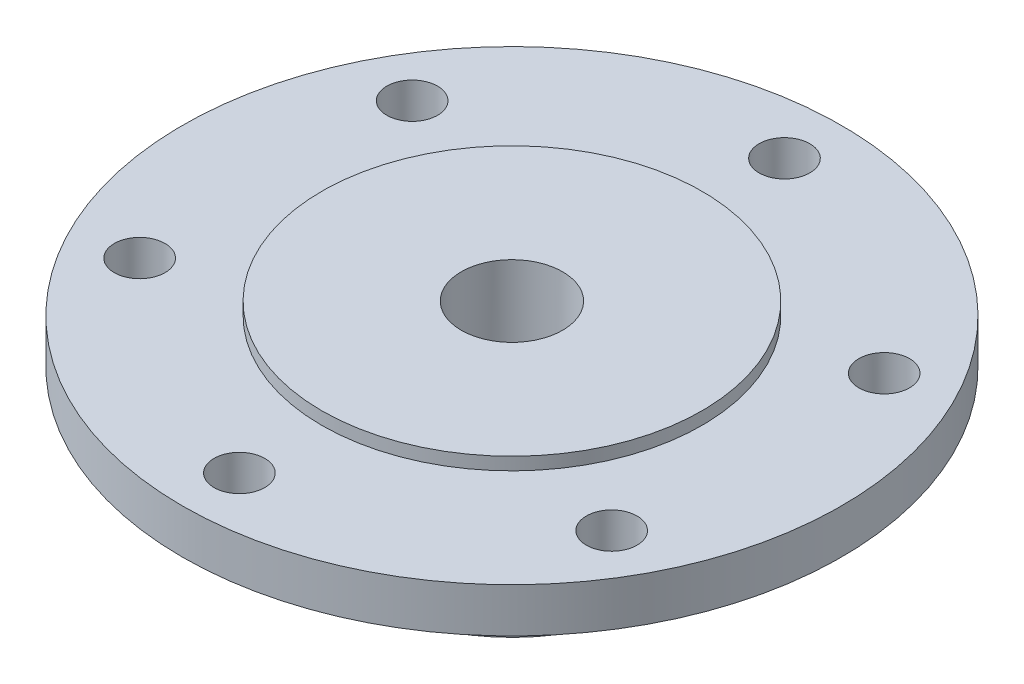
SolidWorks part; units mm, degrees
ref_plane "Front Plane" through (0, 0, 0) normal (0, 0, 1) x (1, 0, 0)
ref_plane "Top Plane" through (0, 0, 0) normal (0, 1, 0) x (1, 0, 0)
ref_plane "Right Plane" through (0, 0, 0) normal (1, 0, 0) x (0, 0, -1)
sketch "Sketch1" plane through (0, 0, 0) normal (0, 0, 1) x (1, 0, 0)
  line L0 (0, 11.2335) -> (0, -11.2335) construction
  line L1 (0, 7.25) -> (0, -7.25)
  line L2 (0, 7.25) -> (15, 7.25)
  line L3 (15, 7.25) -> (15, 6.25)
  line L4 (15, 6.25) -> (26, 6.25)
  line L5 (26, 6.25) -> (26, 2.75)
  line L6 (26, 2.75) -> (12, 2.75)
  line L7 (0, -7.25) -> (12, -7.25)
  line L8 (12, -7.25) -> (12, 2.75)
  point P4 (0, 0)
  point P8 (0, 0)
  dimension "D1" = 12
  dimension "D2" = 15
  dimension "D3" = 26
  dimension "D4" = 2.75
  dimension "D5" = 6.25
  dimension "D6" = 7.25
revolve "Revolve1" add sketch "Sketch1" angle 360 about L0
hole_wizard "Tap Drill for M12x1.25 Tap1" positions "Sketch3" profile "Sketch4" hole size "M12x1.25" standard "ANSI Metric"
sketch "Sketch3" plane through (0, -7.25, 0) normal (0, -1, 0) x (-1, 0, 0)
  point P0 (0, 0)
sketch "Sketch4" plane through (0, -7.25, 0) normal (1, 0, 0) x (0, 0, -1)
  line L0 (0, 0) -> (0, 11)
  line L1 (0, 11) -> (6, 7.3948)
  line L2 (6, 7.3948) -> (6, 0)
  line L5 (6, 0) -> (0, 0)
  line L10 (0, 11) -> (-6, 7.3948) construction
  line L11 (0, -6.35) -> (0, 107.95) construction
  dimension "Hole Dia." = 12
  dimension "Hole Depth" = 11
  dimension "Drill Angle" = 118
sketch "Sketch5" plane through (0, 7.25, 0) normal (0, 1, 0) x (1, 0, 0)
  circle A0 centre (0, 0) radius 4
  circle A1 centre (0, 0) radius 15 construction
  dimension "D1" = 8
extrude "Cut-Extrude1" cut sketch "Sketch5" against normal through all
sketch "Sketch6" plane through (0, 2.75, 0) normal (0, -1, 0) x (1, 0, 0)
  circle A1 centre (-18.6195, 10.75) radius 2
  circle A2 centre (0, 21.5) radius 2
  circle A3 centre (18.6195, 10.75) radius 2
  circle A4 centre (18.6195, -10.75) radius 2
  circle A5 centre (0, -21.5) radius 2
  circle A6 centre (-18.6195, -10.75) radius 2
  circle A7 centre (0, 0) radius 26 construction
  dimension "D1" = 6
  dimension "D2" = 4
  dimension "D3" = 18.6195
  dimension "D4" = 18.6195
  dimension "D5" = 10.75
extrude "Cut-Extrude2" cut sketch "Sketch6" against normal through all both and the other way through all
